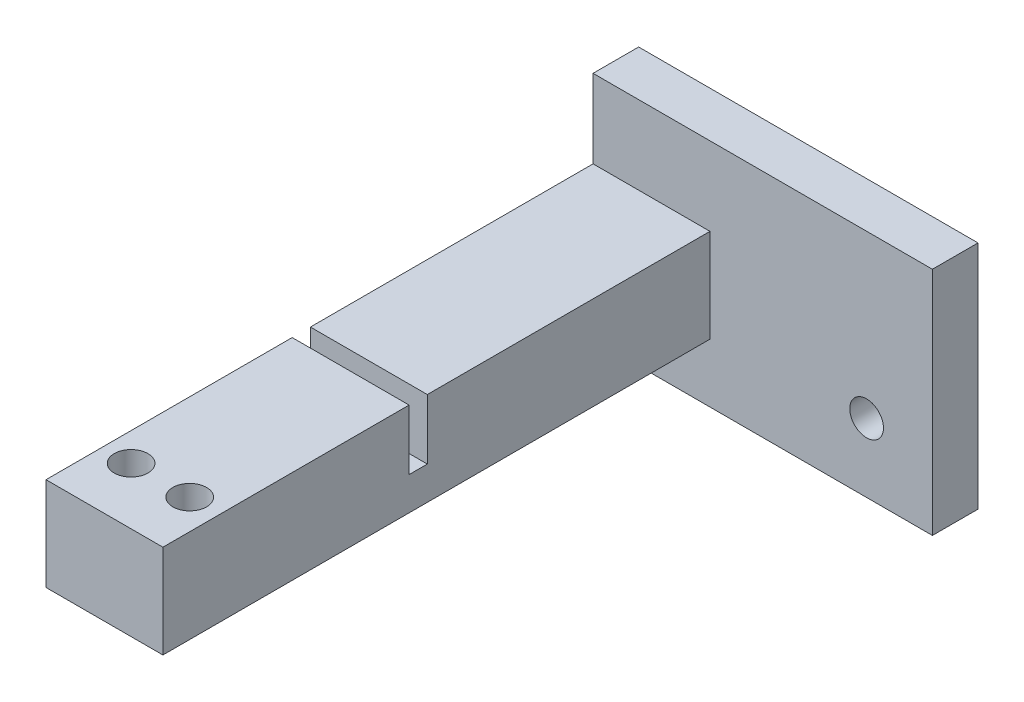
SolidWorks part; units mm, degrees
ref_plane "Alzado" through (0, 0, 0) normal (0, 0, 1) x (1, 0, 0)
ref_plane "Planta" through (0, 0, 0) normal (0, 1, 0) x (1, 0, 0)
ref_plane "Vista lateral" through (0, 0, 0) normal (1, 0, 0) x (0, 0, -1)
sketch "Croquis2" plane through (0, 0, 0) normal (0, 0, 1) x (1, 0, 0)
  line L1 (-7.6339, -227.6309) -> (29.5857, -227.6309)
  line L2 (-7.6339, -227.6309) -> (-7.6339, -252.9206)
  line L3 (-7.6339, -252.9206) -> (29.5857, -252.9206)
  line L4 (29.5857, -227.6309) -> (29.5857, -252.9206)
extrude "Saliente-Extruir1" add sketch "Croquis2" along normal blind 5
sketch "Croquis3" plane through (0, 0, 5) normal (0, 0, 1) x (1, 0, 0)
  line L0 (-7.6339, -227.6309) -> (-7.6339, -252.9206) construction
  line L1 (-7.6339, -236.2306) -> (5.1889, -236.2306)
  line L2 (-7.6339, -236.2306) -> (-7.6339, -246.4725)
  line L3 (-7.6339, -246.4725) -> (5.1889, -246.4725)
  line L4 (5.1889, -236.2306) -> (5.1889, -246.4725)
extrude "Saliente-Extruir2" add sketch "Croquis3" along normal blind 60
sketch "Croquis4" plane through (-7.6339, 0, 0) normal (-1, 0, 0) x (0, 0, 1)
  line L0 (38, -235.2787) -> (38, -236.8351) construction
  line L1 (38, -236.0569) -> (36, -236.0569)
  line L2 (38, -236.0569) -> (38, -242.8351)
  line L3 (38, -242.8351) -> (36, -242.8351)
  line L4 (36, -236.0569) -> (36, -242.8351)
extrude "Cortar-Extruir1" cut sketch "Croquis4" against normal blind 60
sketch "Croquis5" plane through (0, 0, 5) normal (0, 0, 1) x (1, 0, 0)
  circle A0 centre (-2.7952, -249.8624) radius 1.85
  circle A1 centre (22.3692, -245.4021) radius 1.85
  dimension "D1" = 3.7
  dimension "D2" = 3.7
extrude "Cortar-Extruir2" cut sketch "Croquis5" against normal up to surface (5 mm away)
sketch "Croquis6" plane through (0, -236.2306, 0) normal (0, 1, 0) x (1, 0, 0)
  circle A0 centre (1.9055, -58.7782) radius 1.85
  circle A1 centre (-4.5231, -58.7782) radius 1.85
  dimension "D1" = 3.7
  dimension "D2" = 3.7
extrude "Cortar-Extruir3" cut sketch "Croquis6" against normal through all
